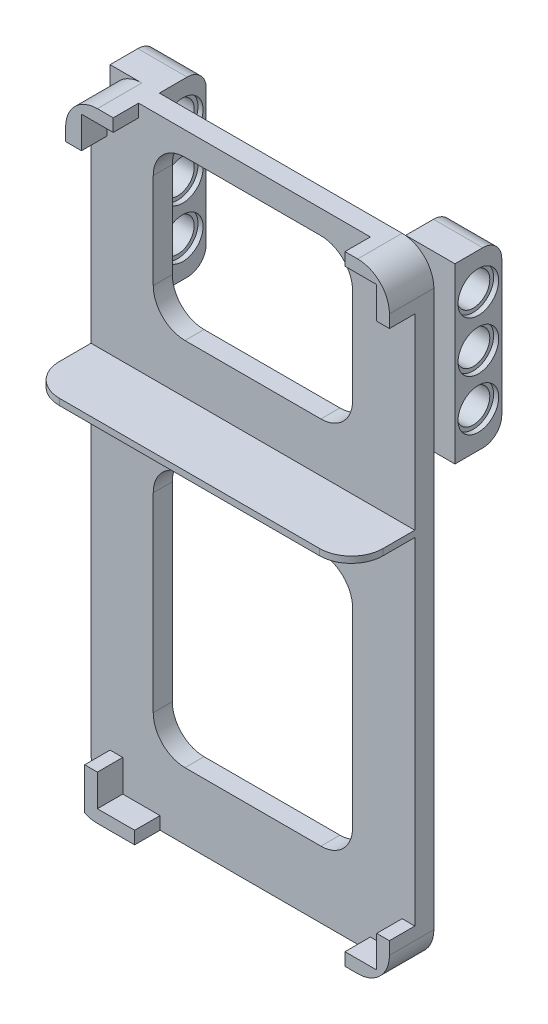
SolidWorks part; units mm, degrees
material "ABS"
ref_plane "Front Plane" through (0, 0, 0) normal (0, 0, 1) x (1, 0, 0)
ref_plane "Top Plane" through (0, 0, 0) normal (0, 1, 0) x (1, 0, 0)
ref_plane "Right Plane" through (0, 0, 0) normal (1, 0, 0) x (0, 0, -1)
sketch "Sketch1" plane through (0, 0, 0) normal (0, 0, 1) x (1, 0, 0)
  line L0 (25.5, 97.5) -> (25.5, 61) construction
  line L1 (0, 0) -> (51, 0)
  line L2 (0, 0) -> (0, 97.5)
  line L3 (0, 97.5) -> (51, 97.5)
  line L4 (51, 0) -> (51, 97.5)
  line L5 (0, 61) -> (51, 61)
  line L6 (51, 61) -> (51, 60)
  line L7 (51, 60) -> (0, 60)
  line L8 (0, 60) -> (0, 61)
  line L9 (51, 61) -> (51, 60)
  line L10 (0, 60) -> (0, 61)
  line L11 (51, 60) -> (51, 61)
  line L12 (25.5, 60) -> (25.5, 0) construction
  dimension "D1" = 97.5
  dimension "D2" = 51
  dimension "D3" = 36.5
  dimension "D4" = 60
extrude "Boss-Extrude2" add sketch "Sketch1" along normal blind 3 contours L2 L1 L4 L3
sketch "Sketch3" plane through (0, 0, 3) normal (0, 0, 1) x (1, 0, 0)
  line L0 (0, 97.5) -> (7.5, 97.5)
  line L1 (0, 97.5) -> (51, 97.5) construction
  line L2 (7.5, 97.5) -> (7.5, 95.5)
  line L3 (7.5, 95.5) -> (2.5, 95.5)
  line L4 (2.5, 95.5) -> (2.5, 90.5)
  line L5 (2.5, 90.5) -> (0, 90.5)
  line L6 (0, 0) -> (0, 97.5) construction
  line L7 (0, 90.5) -> (0, 97.5)
  line L8 (51, 97.5) -> (44, 97.5)
  line L9 (44, 97.5) -> (44, 95.5)
  line L10 (44, 95.5) -> (49, 95.5)
  line L11 (49, 95.5) -> (49, 90.5)
  line L12 (49, 90.5) -> (51, 90.5)
  line L13 (51, 0) -> (51, 97.5) construction
  line L14 (51, 90.5) -> (51, 97.5)
  line L16 (0, 0) -> (51, 0) construction
  line L22 (51, 0) -> (44, 0)
  line L23 (44, 0) -> (44, 2)
  line L24 (44, 2) -> (49, 2)
  line L25 (49, 2) -> (49, 7)
  line L26 (49, 7) -> (51, 7)
  line L27 (51, 7) -> (51, 0)
  dimension "D1" = 2
  dimension "D2" = 2.5
  dimension "D3" = 5
  dimension "D4" = 5
  dimension "D5" = 2
  dimension "D6" = 2
  dimension "D7" = 5
  dimension "D8" = 5
  dimension "D13" = 2
  dimension "D14" = 2
  dimension "D15" = 5
  dimension "D16" = 5
extrude "Boss-Extrude3" add sketch "Sketch3" along normal blind 4
sketch "Sketch4" plane through (0, 0, 3) normal (0, 0, 1) x (1, 0, 0)
  line L0 (3, 0) -> (3, 7)
  line L1 (0, 0) -> (51, 0) construction
  line L2 (3, 7) -> (5, 7)
  line L3 (5, 7) -> (5, 2)
  line L4 (5, 2) -> (10.8695, 2)
  line L5 (10.8695, 2) -> (10.8695, 0)
  line L6 (10.8695, 0) -> (3, 0)
  line L7 (0, 0) -> (0, 97.5) construction
  dimension "D1" = 5
  dimension "D2" = 2
  dimension "D3" = 2
  dimension "D4" = 3
extrude "Boss-Extrude4" add sketch "Sketch4" along normal blind 4 contours L6 L0 L2 L3 L4 L5
sketch "Sketch5" plane through (0, 0, 3) normal (0, 0, 1) x (1, 0, 0)
  line L0 (0, 61) -> (51, 61)
  line L1 (51, 61) -> (51, 60)
  line L2 (51, 60) -> (0, 60)
  line L3 (0, 60) -> (0, 61)
  line L4 (17.8264, 61) -> (17.8264, 60)
  line L5 (17.8264, 60) -> (33.5132, 60)
  line L6 (33.5132, 60) -> (33.5132, 61)
  line L7 (33.5132, 61) -> (17.8264, 61)
extrude "Boss-Extrude5" add sketch "Sketch5" along normal blind 10 contours L3 L0 L1 L2
sketch "Sketch6" plane through (0, 0, 3) normal (0, 0, 1) x (1, 0, 0)
  line L0 (39.8, 93.7705) -> (9.8, 93.7705)
  line L1 (9.8, 93.7705) -> (9.8, 68.7705)
  line L2 (9.8, 68.7705) -> (41.2, 68.7705)
  line L3 (41.2, 68.7705) -> (41.2, 93.7705)
  line L4 (41.2, 93.7705) -> (39.8, 93.7705)
  line L5 (0, 0) -> (0, 97.5) construction
  line L7 (51, 0) -> (51, 97.5) construction
  line L9 (0, 0) -> (51, 0) construction
  line L10 (39.8, 50.5) -> (9.8, 50.5)
  line L11 (9.8, 50.5) -> (9.8, 10.5)
  line L12 (9.8, 10.5) -> (41.2, 10.5)
  line L13 (41.2, 10.5) -> (41.2, 50.5)
  line L14 (41.2, 50.5) -> (39.8, 50.5)
  line L15 (51, 60) -> (0, 60) construction
  dimension "D1" = 25
  dimension "D2" = 30
  dimension "D3" = 9.8
  dimension "D4" = 9.8
  dimension "D5" = 40
  dimension "D6" = 30
  dimension "D7" = 10.5
  dimension "D8" = 9.5
extrude "Cut-Extrude1" cut sketch "Sketch6" against normal blind 10 contours L4 L0 L1 L2 L3 | L10 L11 L12 L13 L14
fillet "Fillet1" radius 5 14 edges at (0, 60.5, 13) (51, 60.5, 13) (9.8, 50.5, 1.5) (9.8, 93.7705, 1.5) (41.2, 93.7705, 1.5) (41.2, 10.5, 1.5) (9.8, 10.5, 1.5) (41.2, 50.5, 1.5) (51, 0, 3.5) (51, 97.5, 3.5) (0, 97.5, 3.5) (9.8, 68.7705, 1.5) (41.2, 68.7705, 1.5) (0, 0, 1.5)
sketch "Sketch7" plane through (51, 0, 0) normal (1, 0, 0) x (0, 0, -1)
  line L0 (-3, 7) -> (-3, 60) construction
  line L1 (-3, 45) -> (0, 45)
  line L2 (0, 60) -> (0, 0) construction
  line L3 (0, 45) -> (0, 75)
  line L4 (0, 0) -> (0, 97.5) construction
  line L5 (0, 75) -> (-3, 75)
  line L6 (-3, 61) -> (-3, 90.5) construction
  line L7 (-3, 75) -> (-3, 45)
  line L8 (-7, 5) -> (0, 5) construction
  line L9 (0, 92.5) -> (-7, 92.5) construction
  dimension "D2" = 40
  dimension "D3" = 17.5
sketch "Sketch8" plane through (0, 0, 0) normal (-1, 0, 0) x (0, 0, 1)
  line L0 (0, 89.53) -> (0, 62.21)
  line L1 (0, 97.5) -> (-7.38, 97.5)
  line L2 (0, 97.5) -> (0, 70.18)
  line L3 (0, 70.18) -> (-7.38, 70.18)
  line L4 (-7.38, 97.5) -> (-7.38, 70.18)
  line L5 (0, 81.56) -> (0, 54.24)
  circle A1 centre (-3.69, 91.81) radius 2.6
  circle A2 centre (-3.69, 83.84) radius 2.6
  circle A3 centre (-3.69, 75.87) radius 2.6
  line M10 (0, 92.5) -> (0, 5)
  dimension "D3" = 3.69
  dimension "D2" = 5.2
  dimension "D4" = 5.69
  dimension "D1" = 7.38
  dimension "D6" = 27.32
  dimension "D5" = 3
extrude "Boss-Extrude6" add sketch "Sketch8" against normal blind 7.76 contours L1 L4 L3 L2 A3 A2 A1 M10
sketch "Sketch9" plane through (0, 0, 0) normal (-1, 0, 0) x (0, 0, 1)
  circle A0 centre (-3.69, 91.81) radius 3.2
  circle A1 centre (-3.69, 83.84) radius 3.2
  circle A2 centre (-3.69, 75.87) radius 3.2
  dimension "D1" = 6.4
  dimension "D2" = 6.4
  dimension "D3" = 6.4
extrude "Cut-Extrude2" cut sketch "Sketch9" against normal blind 0.8 contours A0 | A1 | A2
sketch "Sketch10" plane through (7.76, 0, 0) normal (1, 0, 0) x (0, 0, -1)
  circle A0 centre (3.69, 91.81) radius 3.2
  circle A1 centre (3.69, 83.84) radius 3.2
  circle A2 centre (3.69, 75.87) radius 3.2
  dimension "D1" = 6.4
  dimension "D2" = 6.4
  dimension "D3" = 6.4
extrude "Cut-Extrude3" cut sketch "Sketch10" against normal blind 0.8 contours A0 | A1 | A2
ref_plane "Plane1" through (25.5, 0, 0) normal (1, 0, 0) x (0, 0, -1)
ref_plane "Plane2" through (27.16, 0, 0) normal (1, 0, 0) x (0, 0, -1)
mirror "Mirror2" about plane through (27.16, 0, 0) normal (1, 0, 0) of "Cut-Extrude2", "Cut-Extrude3", "Boss-Extrude6"
fillet "Fillet2" radius 3 4 edges at (3.88, 70.18, -7.38) (50.44, 70.18, -7.38) (3.88, 97.5, -7.38) (50.44, 97.5, -7.38)
